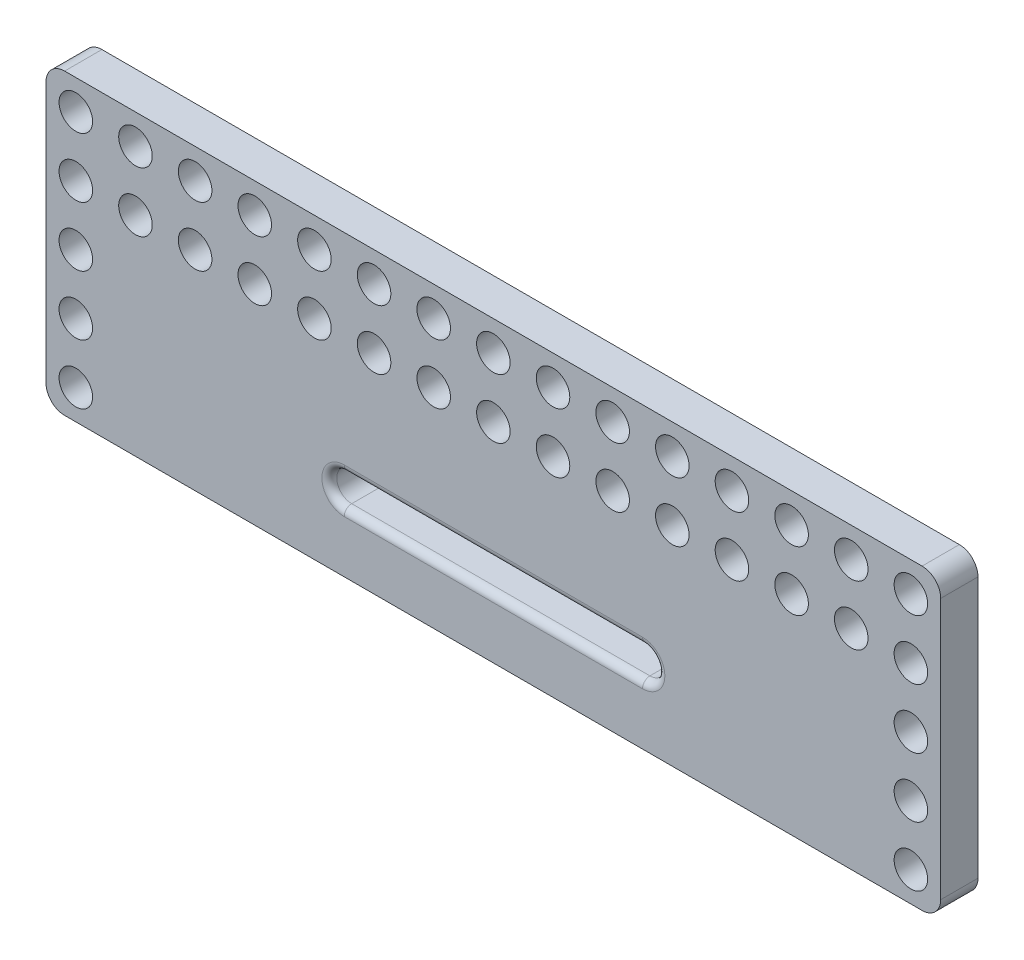
SolidWorks part; units mm, degrees
ref_plane "前视基准面" through (0, 0, 0) normal (0, 0, 1) x (1, 0, 0)
ref_plane "上视基准面" through (0, 0, 0) normal (0, 1, 0) x (1, 0, 0)
ref_plane "右视基准面" through (0, 0, 0) normal (1, 0, 0) x (0, 0, -1)
sketch "草图1" plane through (0, 0, 0) normal (0, 0, 1) x (1, 0, 0)
  line L0 (0, 0) -> (0, 30336.2514) construction
  line L3 (-60, -20) -> (60, -20)
  line L5 (-60, 20) -> (60, -20) construction
  line L6 (-60, -20) -> (60, 20) construction
  line L7 (20, -8) -> (-20, -8)
  line L8 (-20, -12) -> (20, -12)
  line L9 (-60, 20) -> (60, 20)
  line L13 (-56, -16) -> (-56, -8) construction
  line L14 (-56, 16) -> (-48, 16) construction
  line L36 (-60, 20) -> (-60, -20)
  line L37 (60, 20) -> (60, -20)
  arc A0 (-20, -8) -> (-20, -12) centre (-20, -10) ccw
  arc A1 (20, -8) -> (20, -12) centre (20, -10) cw
  circle A2 centre (-56, -16) radius 2.25
  circle A3 centre (-56, -8) radius 2.25
  circle A4 centre (-56, 0) radius 2.25
  circle A5 centre (-56, 8) radius 2.25
  circle A6 centre (-56, 16) radius 2.25
  circle A7 centre (56, 16) radius 2.25
  circle A8 centre (56, 8) radius 2.25
  circle A9 centre (56, 0) radius 2.25
  circle A10 centre (56, -16) radius 2.25
  circle A11 centre (56, -8) radius 2.25
  circle A12 centre (-48, 16) radius 2.25
  circle A13 centre (-48, 8) radius 2.25
  circle A14 centre (-40, 16) radius 2.25
  circle A15 centre (-40, 8) radius 2.25
  circle A16 centre (-32, 16) radius 2.25
  circle A17 centre (-32, 8) radius 2.25
  circle A18 centre (-24, 16) radius 2.25
  circle A19 centre (-24, 8) radius 2.25
  circle A20 centre (-16, 16) radius 2.25
  circle A21 centre (-16, 8) radius 2.25
  circle A22 centre (-8, 16) radius 2.25
  circle A23 centre (-8, 8) radius 2.25
  circle A24 centre (0, 16) radius 2.25
  circle A25 centre (0, 8) radius 2.25
  circle A26 centre (8, 16) radius 2.25
  circle A27 centre (8, 8) radius 2.25
  circle A28 centre (16, 16) radius 2.25
  circle A29 centre (16, 8) radius 2.25
  circle A30 centre (24, 16) radius 2.25
  circle A31 centre (24, 8) radius 2.25
  circle A32 centre (32, 16) radius 2.25
  circle A33 centre (32, 8) radius 2.25
  circle A34 centre (40, 16) radius 2.25
  circle A35 centre (40, 8) radius 2.25
  circle A36 centre (48, 16) radius 2.25
  circle A37 centre (48, 8) radius 2.25
  point P0 (0, 0)
  point P16 (0, 0)
  point P18 (0, 0)
  point P21 (0, 0)
  dimension "D1" = 20
  dimension "D5" = 2
  dimension "D7" = 4
  dimension "D8" = 4.5
  dimension "D13" = 4
  dimension "D2" = 120
  dimension "D3" = 40
  dimension "D4" = 10
  dimension "D6" = 40
  dimension "D10" = 8
  dimension "D12" = 8
  dimension "D9" = 5
  dimension "D11" = 14
extrude "凸台-拉伸1" add sketch "草图1" along normal blind 5
fillet "圆角1" radius 2.5 4 edges at (60, 20, 2.5) (60, -20, 2.5) (-60, -20, 2.5) (-60, 20, 2.5)
fillet "圆角2" radius 1 4 edges at (0, -8, 5) (-22, -10, 5) (0, -12, 5) (22, -10, 5)
